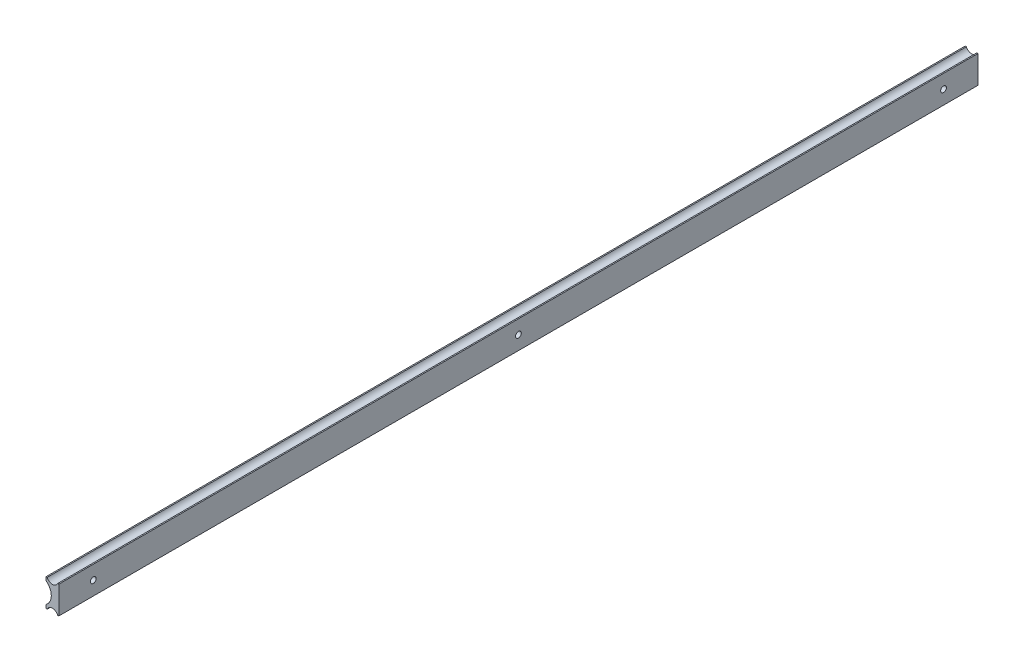
SolidWorks part; units mm, degrees
material "6061 合金"
ref_plane "前视基准面" through (0, 0, 0) normal (0, 0, 1) x (1, 0, 0)
ref_plane "上视基准面" through (0, 0, 0) normal (0, 1, 0) x (1, 0, 0)
ref_plane "右视基准面" through (0, 0, 0) normal (1, 0, 0) x (0, 0, -1)
sketch "草图1" plane through (0, 0, 0) normal (0, 0, 1) x (1, 0, 0)
  line L1 (-2.8, -6) -> (2.8, -6)
  line L2 (-2.8, -6) -> (-2.8, 6)
  line L3 (-2.8, 6) -> (2.8, 6)
  line L4 (2.8, -6) -> (2.8, 6)
  line L5 (0, 6) -> (0, -6) construction
  line L6 (-2.8, 0) -> (2.8, 0) construction
  point P0 (0, 0)
  dimension "D1" = 5.6
  dimension "D2" = 12
extrude "凸台-拉伸1" add sketch "草图1" along normal mid plane 400
sketch "草图2" plane through (0, 0, 0) normal (0, 0, 1) x (1, 0, 0)
  line L0 (0, 7) -> (0, 0) construction
  circle A0 centre (0, 7) radius 2.5
  dimension "D2" = 5
  dimension "D1" = 7
extrude "切除-拉伸1" cut sketch "草图2" against normal mid plane 460
mirror "镜向1" about plane through (0, 0, 0) normal (0, 1, 0) of "切除-拉伸1"
sketch "草图3" plane through (0, 0, 200) normal (0, 0, 1) x (1, 0, 0)
  line L0 (-6, 0) -> (0, 0) construction
  circle A0 centre (-6, 0) radius 5.5
  dimension "D2" = 11
  dimension "D1" = 6
extrude "切除-拉伸2" cut sketch "草图3" against normal mid plane 1380
sketch "草图4" plane through (2.8, 0, 0) normal (1, 0, 0) x (0, 0, -1)
  line L0 (-185, 0) -> (185, 0) construction
  point P4 (0, 0)
  dimension "D1" = 370
hole_wizard "M3 螺纹孔1" positions "草图5" profile "草图6" tap size "M3" standard "GB" end condition through all
sketch "草图5" plane through (2.8, 0, 0) normal (1, 0, 0) x (0, 0, -1)
  point P0 (-185, 0)
  point P3 (0, 0)
  point P6 (185, 0)
sketch "草图6" plane through (2.8, 0, 185) normal (0, 1, 0) x (0, 0, -1)
  line L0 (0, 0) -> (0, 5.6)
  line L1 (0, 5.6) -> (1.25, 5.6)
  line L2 (1.25, 5.6) -> (1.25, 0)
  line L5 (1.25, 0) -> (0, 0)
  line L11 (0, -6.35) -> (0, 107.95) construction
  dimension "通孔螺纹孔钻头直径" = 2.5
  dimension "通孔螺纹孔钻头深度" = 5.6
cosmetic thread "孔螺蚊线1" parameters "D2"=3
cosmetic thread "孔螺蚊线2" parameters "D2"=3
cosmetic thread "孔螺蚊线3" parameters "D2"=3
